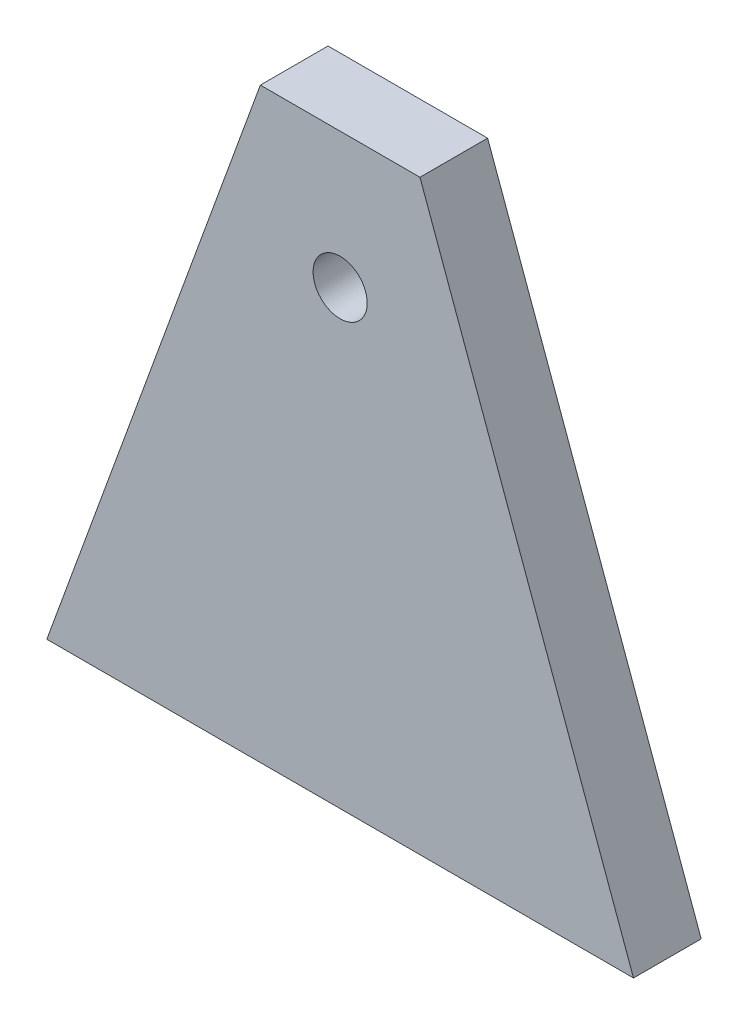
SolidWorks part; units mm, degrees
material "Pinho"
ref_plane "Plano frontal" through (0, 0, 0) normal (0, 0, 1) x (1, 0, 0)
ref_plane "Plano superior" through (0, 0, 0) normal (0, 1, 0) x (1, 0, 0)
ref_plane "Plano direito" through (0, 0, 0) normal (1, 0, 0) x (0, 0, -1)
sketch "Esboço1" plane through (0, 0, 0) normal (0, 0, 1) x (1, 0, 0)
  line L0 (0, 0) -> (130, 0)
  line L1 (130, 0) -> (82.6839, 130)
  line L2 (82.6839, 130) -> (47.3161, 130)
  line L3 (47.3161, 130) -> (0, 0)
  dimension "D1" = 130
  dimension "D2" = 130
  dimension "D3" = 70
  dimension "D4" = 70
  dimension "D5" = 35.3677
extrude "Ressalto-extrusão1" add sketch "Esboço1" along normal blind 15
sketch "Esboço2" plane through (0, 0, 15) normal (0, 0, 1) x (1, 0, 0)
  line L0 (65, 130) -> (65, 0) construction
  line L1 (82.6839, 130) -> (47.3161, 130) construction
  line L2 (0, 0) -> (130, 0) construction
  circle A0 centre (65, 100) radius 6
  dimension "D1" = 12
  dimension "D2" = 30
extrude "Corte-extrusão1" cut sketch "Esboço2" against normal through all
